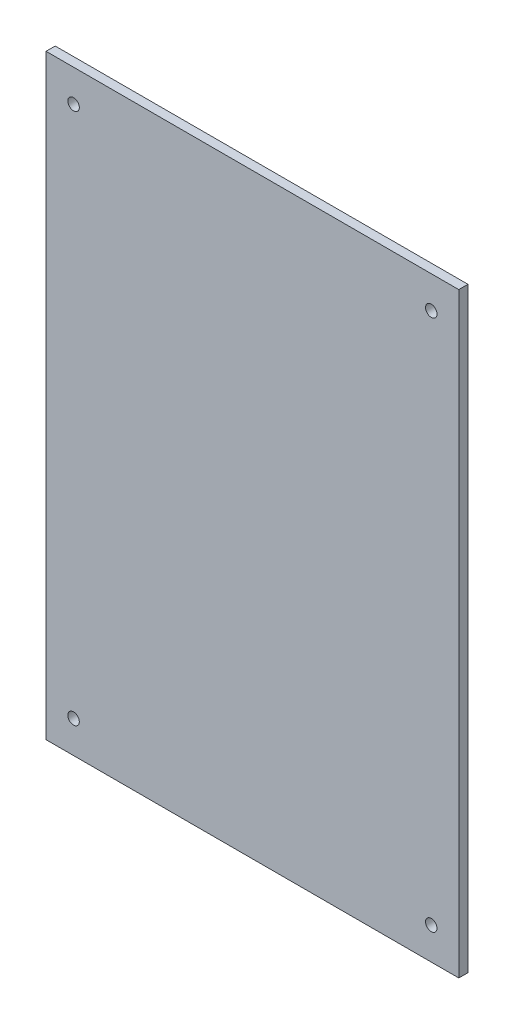
SolidWorks part; units mm, degrees
ref_plane "Front Plane" through (0, 0, 0) normal (0, 0, 1) x (1, 0, 0)
ref_plane "Top Plane" through (0, 0, 0) normal (0, 1, 0) x (1, 0, 0)
ref_plane "Right Plane" through (0, 0, 0) normal (1, 0, 0) x (0, 0, -1)
sketch "Sketch1" plane through (0, 0, 0) normal (0, 0, 1) x (1, 0, 0)
  line L1 (0, 0) -> (180, 0)
  line L2 (0, 0) -> (0, 260)
  line L3 (0, 260) -> (180, 260)
  line L4 (180, 0) -> (180, 260)
  circle A0 centre (12, 14) radius 2.5
  circle A1 centre (12, 246) radius 2.5
  circle A2 centre (168, 14) radius 2.5
  circle A3 centre (168, 246) radius 2.5
  dimension "D1" = 5
  dimension "D2" = 12
  dimension "D3" = 168
  dimension "D4" = 180
  dimension "D5" = 14
  dimension "D6" = 246
  dimension "D7" = 260
extrude "Profile" add sketch "Sketch1" along normal blind 4
equation "\"Profile_Depth\" = 4mm"
equation "\"D1@Profile\" = \"Profile_Depth\""
equation "\"EnvelopeWidth\" = 180mm"
equation "\"EnvelopeHeight\" = 260mm"
